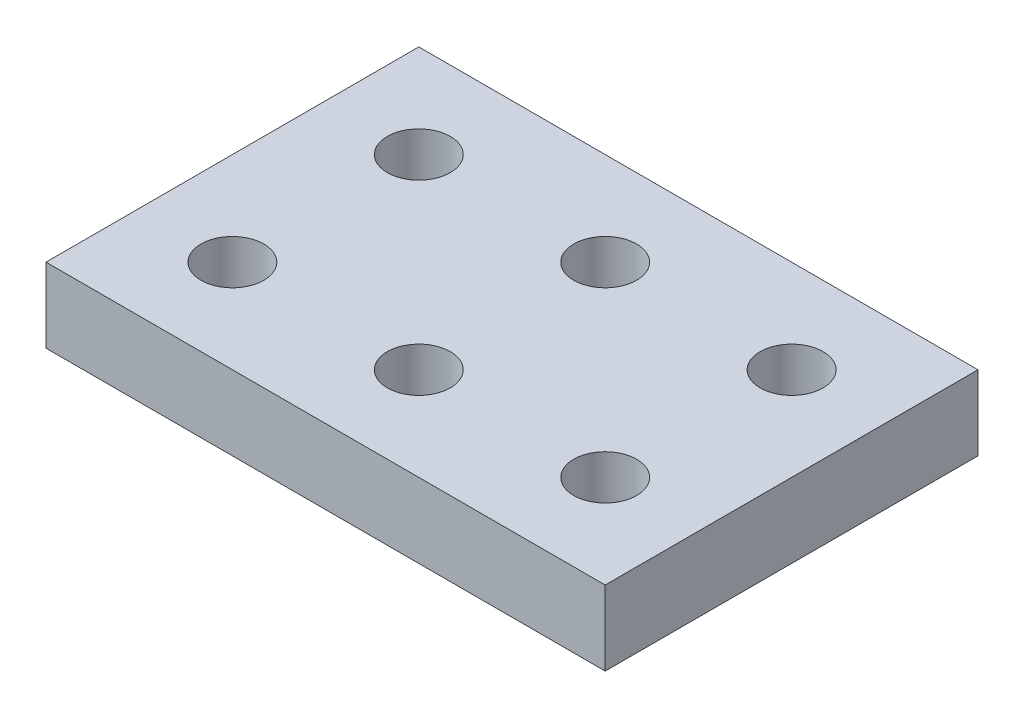
SolidWorks part; units mm, degrees
ref_plane "前视基准面" through (0, 0, 0) normal (0, 0, 1) x (1, 0, 0)
ref_plane "上视基准面" through (0, 0, 0) normal (0, 1, 0) x (1, 0, 0)
ref_plane "右视基准面" through (0, 0, 0) normal (1, 0, 0) x (0, 0, -1)
sketch "草图1" plane through (0, 0, 0) normal (0, 1, 0) x (1, 0, 0)
  line L1 (0, 0) -> (240, 0)
  line L2 (0, 0) -> (0, 160)
  line L3 (0, 160) -> (240, 160)
  line L4 (240, 0) -> (240, 160)
  dimension "D1" = 240
  dimension "D2" = 160
extrude "凸台-拉伸1" add sketch "草图1" along normal blind 32
sketch "草图3" plane through (0, 32, 0) normal (0, 1, 0) x (1, 0, 0)
  line L0 (-1000, 80) -> (49000, 80) construction
  line L1 (0, 160) -> (0, 0) construction
  line L2 (120, -840) -> (120, 49160) construction
  line L3 (240, 160) -> (0, 160) construction
  circle A0 centre (120, 120) radius 13.5
  point P5 (0, 80)
  point P10 (120, 160)
  dimension "D1" = 27
  dimension "D2" = 40
extrude "切除-拉伸2" cut sketch "草图3" against normal through all
pattern_linear "阵列(线性)5" count 2 spacing 80 along (-1, 0, 0) of "切除-拉伸2"
pattern_linear "阵列(线性)6" count 2 spacing 80 along (1, 0, 0) of "切除-拉伸2"
pattern_linear "阵列(线性)7" count 2 spacing 80 along (0, 0, 1) of "切除-拉伸2", "阵列(线性)5", "阵列(线性)6"
